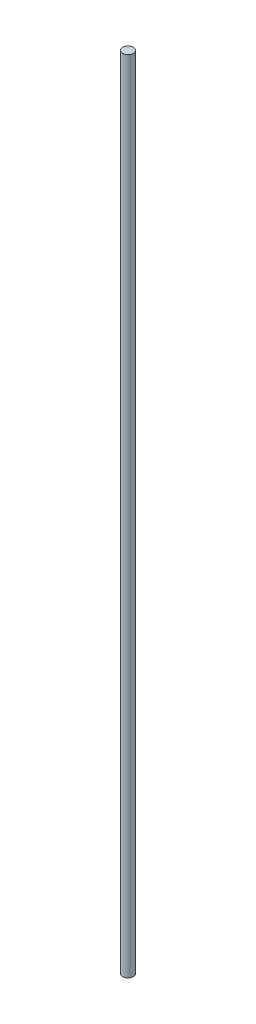
SolidWorks part; units mm, degrees
ref_plane "Front Plane" through (0, 0, 0) normal (0, 0, 1) x (1, 0, 0)
ref_plane "Top Plane" through (0, 0, 0) normal (0, 1, 0) x (1, 0, 0)
ref_plane "Right Plane" through (0, 0, 0) normal (1, 0, 0) x (0, 0, -1)
sketch "Sketch1" plane through (0, 0, 0) normal (0, 1, 0) x (1, 0, 0)
  circle A0 centre (0, 0) radius 5
  dimension "D1" = 10
extrude "Boss-Extrude1" add sketch "Sketch1" along normal blind 750
